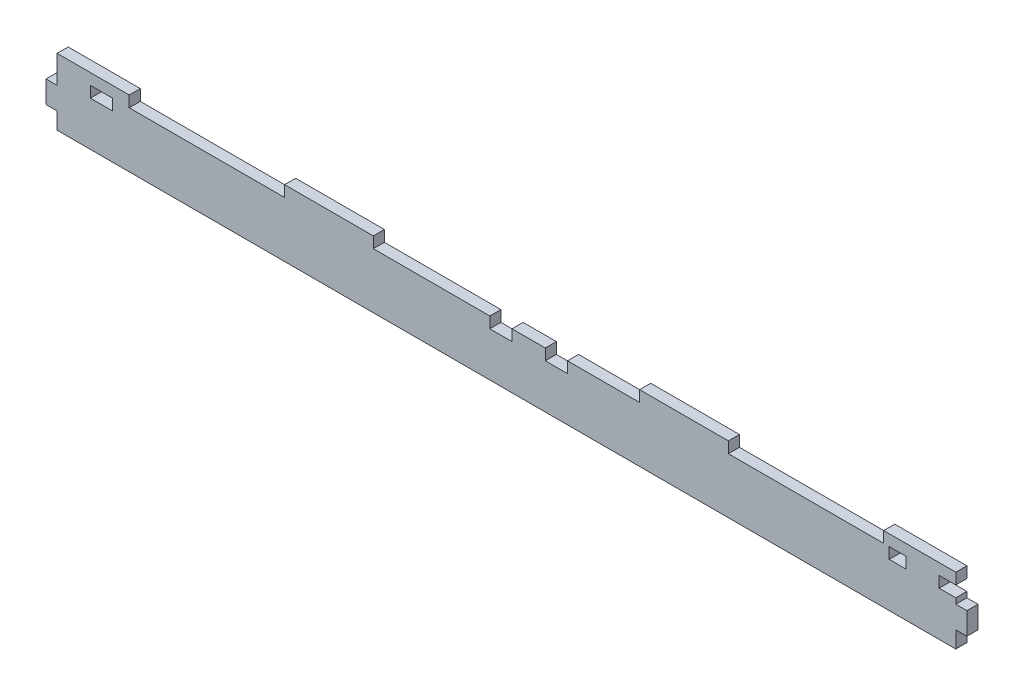
SolidWorks part; units mm, degrees
ref_plane "Front Plane" through (0, 0, 0) normal (0, 0, 1) x (1, 0, 0)
ref_plane "Top Plane" through (0, 0, 0) normal (0, 1, 0) x (1, 0, 0)
ref_plane "Right Plane" through (0, 0, 0) normal (1, 0, 0) x (0, 0, -1)
sketch "Sketch1" plane through (0, 0, 0) normal (0, 0, 1) x (1, 0, 0)
  line L0 (252.5, 195) -> (252.5, 170) construction
  line L1 (277.5, 254.5874) -> (277.5, 116.6829) construction
  line L8 (480, 177.5) -> (485, 177.5)
  line L9 (480, 170) -> (480, 177.5)
  line L11 (447.5, 195) -> (377.5, 195)
  line L12 (480, 190) -> (480, 187.5)
  line L13 (480, 187.5) -> (485, 187.5)
  line L14 (485, 187.5) -> (485, 177.5)
  line L15 (377.5, 200) -> (377.5, 195)
  line L16 (337.5, 200) -> (377.5, 200)
  line L17 (337.5, 195) -> (337.5, 200)
  line L18 (480, 200) -> (480, 195)
  line L19 (447.5, 200) -> (480, 200)
  line L20 (447.5, 195) -> (447.5, 200)
  line L21 (435, 192.1418) -> (435, 212.7842) construction
  line L22 (217.5, 195) -> (270, 195)
  line L25 (107.5, 195) -> (107.5, 200)
  line L26 (107.5, 200) -> (75, 200)
  line L27 (75, 200) -> (75, 195)
  line L29 (217.5, 195) -> (217.5, 200)
  line L30 (217.5, 200) -> (177.5, 200)
  line L31 (177.5, 200) -> (177.5, 195)
  line L40 (70, 187.5) -> (70, 177.5)
  line L43 (75, 187.5) -> (70, 187.5)
  line L48 (430, 182.5) -> (424.9156, 182.5) construction
  line L49 (75, 195) -> (75, 187.5)
  line L50 (107.5, 195) -> (177.5, 195)
  line L58 (75, 170) -> (75, 177.5)
  line L60 (75, 177.5) -> (70, 177.5)
  line L73 (480, 170) -> (75, 170)
  line L75 (450, 195) -> (457.5, 195)
  line L76 (450, 195) -> (450, 190)
  line L77 (450, 190) -> (457.5, 190)
  line L78 (457.5, 195) -> (457.5, 190)
  line L79 (472.5, 195) -> (480, 195)
  line L80 (472.5, 195) -> (472.5, 190)
  line L85 (472.5, 190) -> (480, 190)
  line L103 (295, 195) -> (295, 190)
  line L104 (295, 190) -> (305, 190)
  line L105 (305, 190) -> (305, 195)
  line L107 (270, 195) -> (270, 190)
  line L108 (270, 190) -> (280, 190)
  line L109 (280, 190) -> (280, 195)
  line L110 (305, 195) -> (337.5, 195)
  line L111 (280, 195) -> (295, 195)
  line L113 (90, 195) -> (100, 195)
  line L114 (90, 195) -> (90, 190)
  line L115 (90, 190) -> (100, 190)
  line L116 (100, 195) -> (100, 190)
  point P33 (70, 182.5)
  point P47 (485, 182.5)
  dimension "D1" = 25
extrude "Boss-Extrude1" add sketch "Sketch1" along normal blind 5
